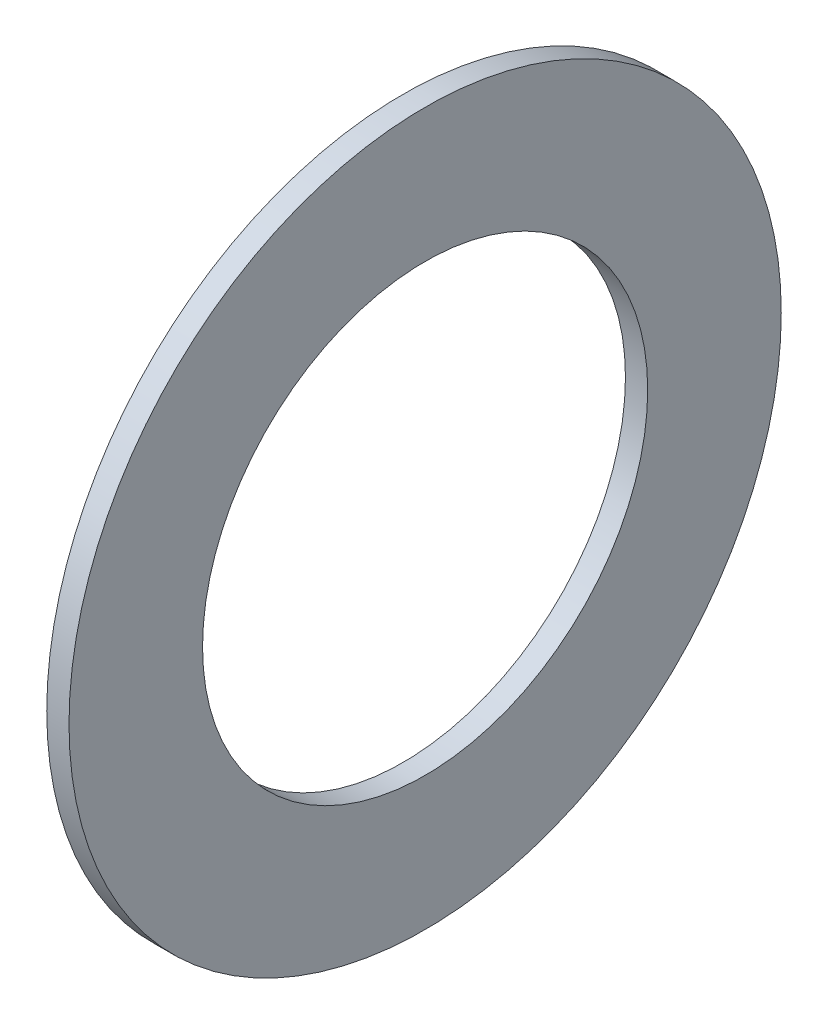
SolidWorks part; units mm, degrees
material "AISI 304"
ref_plane "前视基准面" through (0, 0, 0) normal (0, 0, 1) x (1, 0, 0)
ref_plane "上视基准面" through (0, 0, 0) normal (0, 1, 0) x (1, 0, 0)
ref_plane "右视基准面" through (0, 0, 0) normal (1, 0, 0) x (0, 0, -1)
sketch "草图1" plane through (0, 0, 0) normal (1, 0, 0) x (0, 0, -1)
  circle A0 centre (0, 0) radius 5
  circle A1 centre (0, 0) radius 8
extrude "凸台-拉伸1" add sketch "草图1" along normal blind 0.5
